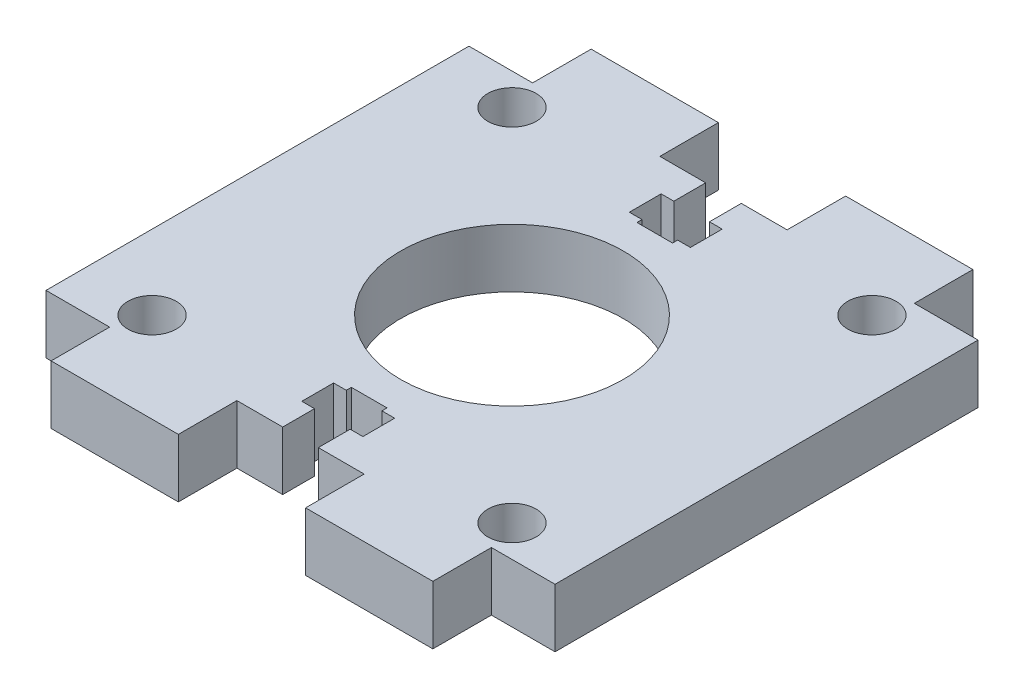
SolidWorks part; units mm, degrees
ref_plane "Front Plane" through (0, 0, 0) normal (0, 0, 1) x (1, 0, 0)
ref_plane "Top Plane" through (0, 0, 0) normal (0, 1, 0) x (1, 0, 0)
ref_plane "Right Plane" through (0, 0, 0) normal (1, 0, 0) x (0, 0, -1)
sketch "Sketch1" plane through (0, 0, 0) normal (0, 1, 0) x (1, 0, 0)
  line L0 (0, 21.1058) -> (0, -21.1058) construction
  line L1 (25.4, -21.1058) -> (19.05, -21.1058)
  line L2 (25.4, -21.1058) -> (25.4, 21.1058)
  line L3 (25.4, 21.1058) -> (19.05, 21.1058)
  line L4 (-25.4, -21.1058) -> (-25.4, 21.1058)
  line L5 (25.4, -21.1058) -> (-25.4, 21.1058) construction
  line L6 (25.4, 21.1058) -> (-25.4, -21.1058) construction
  line L7 (-19.05, -21.1058) -> (-25.4, -21.1058)
  line L8 (-6.35, -26.9478) -> (-19.05, -26.9478)
  line L9 (-6.35, -26.9478) -> (-6.35, -21.1058)
  line L10 (-25.4, 0) -> (25.4, 0) construction
  line L11 (-19.05, -26.9478) -> (-19.05, -21.1058)
  line L12 (-6.35, -26.9478) -> (-19.05, -21.1058) construction
  line L13 (-6.35, -21.1058) -> (-19.05, -26.9478) construction
  line L14 (6.35, -21.1058) -> (19.05, -26.9478) construction
  line L15 (6.35, -26.9478) -> (19.05, -21.1058) construction
  line L16 (19.05, -26.9478) -> (19.05, -21.1058)
  line L17 (6.35, -26.9478) -> (6.35, -21.1058)
  line L18 (6.35, -26.9478) -> (19.05, -26.9478)
  line L19 (-25.4, 21.1058) -> (25.4, -21.1058) construction
  line L20 (6.35, -21.1058) -> (1.778, -21.1058)
  line L21 (6.35, 26.9478) -> (19.05, 21.1058) construction
  line L22 (6.35, 21.1058) -> (19.05, 26.9478) construction
  line L23 (-6.35, 21.1058) -> (-19.05, 26.9478) construction
  line L24 (-6.35, 26.9478) -> (-19.05, 21.1058) construction
  line L25 (6.35, 21.1058) -> (1.778, 21.1058)
  line L26 (6.35, 26.9478) -> (19.05, 26.9478)
  line L27 (6.35, 26.9478) -> (6.35, 21.1058)
  line L28 (19.05, 26.9478) -> (19.05, 21.1058)
  line L29 (-19.05, 26.9478) -> (-19.05, 21.1058)
  line L30 (-6.35, 26.9478) -> (-6.35, 21.1058)
  line L31 (-6.35, 26.9478) -> (-19.05, 26.9478)
  line L32 (-19.05, 21.1058) -> (-25.4, 21.1058)
  line L33 (6.35, 21.1058) -> (1.778, 21.1058)
  line L34 (-1.778, -14.7558) -> (-3.048, -14.7558)
  line L35 (-1.778, -17.9308) -> (-3.048, -17.9308)
  line L36 (1.778, -17.9308) -> (1.778, -21.1058)
  line L37 (1.778, 14.7558) -> (-1.778, 14.2478) construction
  line L38 (-1.778, -17.9308) -> (-1.778, -21.1058)
  line L39 (1.778, -17.9308) -> (-1.778, -21.1058) construction
  line L40 (1.778, -21.1058) -> (-1.778, -17.9308) construction
  line L41 (3.048, -14.7558) -> (1.778, -14.7558)
  line L42 (3.048, -14.7558) -> (3.048, -17.9308)
  line L43 (3.048, -17.9308) -> (1.778, -17.9308)
  line L44 (-3.048, -14.7558) -> (-3.048, -17.9308)
  line L45 (3.048, -14.7558) -> (-3.048, -17.9308) construction
  line L46 (3.048, -17.9308) -> (-3.048, -14.7558) construction
  line L47 (1.778, -14.2478) -> (-1.778, -14.2478)
  line L48 (1.778, -14.2478) -> (1.778, -14.7558)
  line L49 (-1.778, -21.1058) -> (-6.35, -21.1058)
  line L50 (-1.778, -14.2478) -> (-1.778, -14.7558)
  line L51 (1.778, -14.2478) -> (-1.778, -14.7558) construction
  line L52 (1.778, -14.7558) -> (-1.778, -14.2478) construction
  line L53 (0, 7.3323) -> (-6.35, 3.6662) construction
  line L54 (-6.35, 3.6662) -> (-6.35, -3.6662) construction
  line L55 (-6.35, -3.6662) -> (0, -7.3323) construction
  line L56 (0, -7.3323) -> (6.35, -3.6662) construction
  line L57 (6.35, -3.6662) -> (6.35, 3.6662) construction
  line L58 (6.35, 3.6662) -> (0, 7.3323) construction
  line L59 (1.778, 14.2478) -> (-1.778, 14.7558) construction
  line L60 (3.048, 17.9308) -> (-3.048, 14.7558) construction
  line L61 (3.048, 14.7558) -> (-3.048, 17.9308) construction
  line L62 (1.778, 21.1058) -> (-1.778, 17.9308) construction
  line L63 (1.778, 17.9308) -> (-1.778, 21.1058) construction
  line L64 (-1.778, 14.2478) -> (-1.778, 14.7558)
  line L65 (1.778, 14.2478) -> (1.778, 14.7558)
  line L66 (1.778, 14.2478) -> (-1.778, 14.2478)
  line L67 (-3.048, 14.7558) -> (-3.048, 17.9308)
  line L68 (3.048, 17.9308) -> (1.778, 17.9308)
  line L69 (3.048, 14.7558) -> (3.048, 17.9308)
  line L70 (3.048, 14.7558) -> (1.778, 14.7558)
  line L71 (-1.778, 17.9308) -> (-1.778, 21.1058)
  line L72 (1.778, 17.9308) -> (1.778, 21.1058)
  line L73 (-1.778, 17.9308) -> (-3.048, 17.9308)
  line L74 (-1.778, 14.7558) -> (-3.048, 14.7558)
  line L75 (-1.778, 21.1058) -> (-6.35, 21.1058)
  line L76 (-1.778, 21.1058) -> (-6.35, 21.1058)
  line L77 (-17.9605, 17.9605) -> (0, 0) construction
  circle A0 centre (0, 0) radius 11.1125
  circle A1 centre (0, 0) radius 9.525 construction
  circle A2 centre (0, 0) radius 6.35 construction
  circle A3 centre (0, 0) radius 25.4 construction
  circle A4 centre (-17.9605, 17.9605) radius 2.413
  circle A5 centre (17.9605, 17.9605) radius 2.413
  circle A6 centre (17.9605, -17.9605) radius 2.413
  circle A7 centre (-17.9605, -17.9605) radius 2.413
  point P0 (0, 0)
  point P8 (-12.7, -24.0268)
  point P19 (12.7, -24.0268)
  point P28 (12.7, 24.0268)
  point P29 (-12.7, 24.0268)
  point P30 (0, -19.5183)
  point P37 (0, -16.3433)
  point P42 (0, -14.5018)
  point P67 (0, 14.5018)
  point P68 (0, 16.3433)
  point P69 (0, 19.5183)
  point P82 (0, 0)
  dimension "D8" = 22.225
  dimension "D12" = 19.05
  dimension "D13" = 12.7
  dimension "D14" = 50.8
  dimension "D15" = 4.826
  dimension "D1" = 50.8
  dimension "D2" = 42.2116
  dimension "D3" = 5.842
  dimension "D4" = 12.7
  dimension "D5" = 12.7
  dimension "D6" = 3.556
  dimension "D7" = 3.175
  dimension "D9" = 3.175
  dimension "D10" = 6.096
  dimension "D11" = 0.508
  dimension "D16" = 45
  dimension "D17" = 4
extrude "Boss-Extrude1" add sketch "Sketch1" along normal blind 5.842 contours L71 L75 L30 L31 L29 L32 L4 L7 L11 L8 L9 L49 L38 L35 L44 L34 L50 L47 L48 L41 L42 L43 L36 L20 L17 L18 L16 L1 L2 L3 L28 L26 L27 L25 L72 L68 L69 L70 L65 L66 L64 L74 L67 L73
